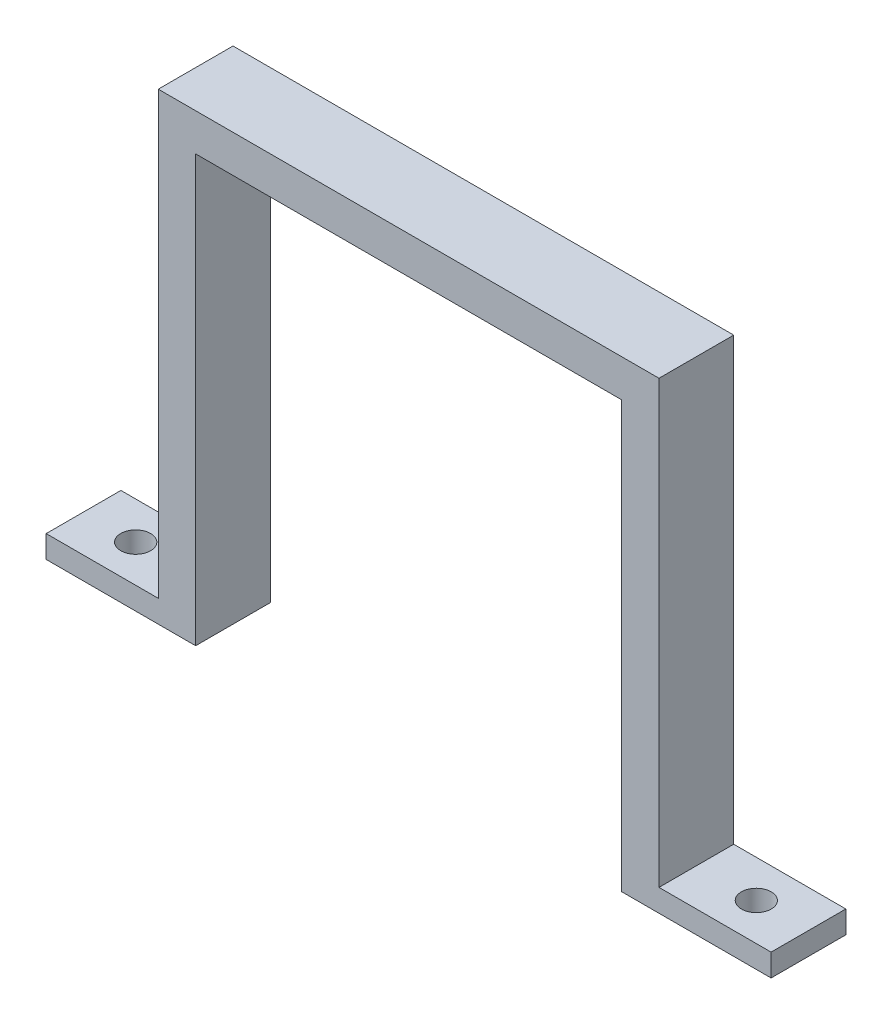
SolidWorks part; units mm, degrees
ref_plane "Front Plane" through (0, 0, 0) normal (0, 0, 1) x (1, 0, 0)
ref_plane "Top Plane" through (0, 0, 0) normal (0, 1, 0) x (1, 0, 0)
ref_plane "Right Plane" through (0, 0, 0) normal (1, 0, 0) x (0, 0, -1)
sketch "Sketch1" plane through (0, 0, 0) normal (0, 0, 1) x (1, 0, 0)
  line L0 (0, -55) -> (0, 55) construction
  line L1 (33.4762, 62) -> (-33.4762, 62)
  line L3 (28.5, 57) -> (-28.5, 57)
  line L5 (55, 0) -> (-55, 0) construction
  line L6 (-33.4762, 62) -> (-33.5, 62)
  line L9 (-33.5, 62) -> (-33.5, 3)
  line L11 (-28.5, 57) -> (-28.5, 0)
  line L12 (-28.5, 0) -> (-48.5, 0)
  line L13 (-48.5, 3) -> (-48.5, 0)
  line L14 (-48.5, 3) -> (-33.5, 3)
  line L15 (33.4762, 62) -> (33.5, 62)
  line L16 (33.5, 62) -> (33.5, 3)
  line L17 (48.5, 3) -> (33.5, 3)
  line L18 (48.5, 3) -> (48.5, 0)
  line L19 (28.5, 0) -> (48.5, 0)
  line L20 (28.5, 57) -> (28.5, 0)
  dimension "D1" = 57
  dimension "D2" = 57
  dimension "D3" = 5
  dimension "D4" = 20
  dimension "D5" = 3
  dimension "D6" = 5
extrude "Boss-Extrude1" add sketch "Sketch1" along normal blind 10
sketch "Sketch4" plane through (0, 0, 0) normal (0, 1, 0) x (1, 0, 0)
  line L0 (0, -9.9532) -> (0, -0.7078) construction
  line L2 (-53.5, -5) -> (53.5, -5) construction
  circle A0 centre (-41.5224, -5) radius 2
  circle A1 centre (41.5224, -5) radius 2
  dimension "D1" = 4
extrude "Cut-Extrude2" cut sketch "Sketch4" along normal blind 10 contours A1 | A0
